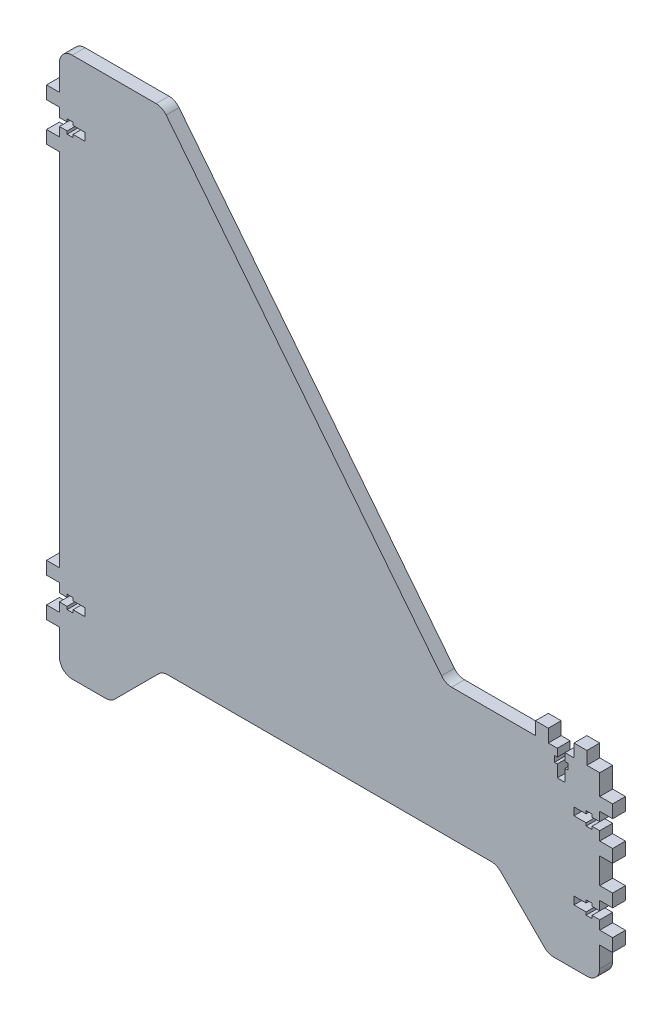
SolidWorks part; units mm, degrees
ref_plane "Plan de face" through (0, 0, 0) normal (0, 0, 1) x (1, 0, 0)
ref_plane "Plan de dessus" through (0, 0, 0) normal (0, 1, 0) x (1, 0, 0)
ref_plane "Plan de droite" through (0, 0, 0) normal (1, 0, 0) x (0, 0, -1)
sketch "Esquisse1" plane through (0, 0, 0) normal (0, 0, 1) x (1, 0, 0)
  line L0 (0, 0) -> (20, 0)
  line L1 (20, 0) -> (20, 71) construction
  line L2 (20, 71) -> (-40, 71) construction
  line L4 (-190, 210) -> (-190, 0) construction
  line L5 (-190, 0) -> (0, 0) construction
  line L6 (-190, 105) -> (56.9095, 105) construction
  line L7 (-190, 210) -> (-150, 210)
  line L8 (-150, 210) -> (-40, 71)
  line L9 (-190, 0) -> (-170, 0)
  line L10 (-170, 0) -> (-150, 20)
  line L11 (-150, 20) -> (-20, 20)
  line L12 (-20, 20) -> (0, 0)
  line L13 (-40, 71) -> (-5, 71)
  line L14 (15, 71) -> (20, 71)
  line L15 (20, 71) -> (20, 63)
  line L16 (20, 43) -> (20, 33)
  line L17 (20, 13) -> (20, 0)
  line L18 (-190, 0) -> (-190, 15)
  line L19 (-190, 35) -> (-190, 175)
  line L20 (-190, 195) -> (-190, 210)
  point P22 (0, 0)
  line B0 (17, 20.4) -> (14.7, 20.4)
  line B1 (14.7, 24.5) -> (10, 24.5)
  line B2 (10, 21.5) -> (14.7, 21.5)
  line B3 (14.7, 20.4) -> (14.7, 21.5)
  line B4 (20, 23) -> (8.7792, 23) construction
  line B5 (20, 21.5) -> (20, 18)
  line B6 (25, 18) -> (25, 13)
  line B7 (25, 13) -> (20, 13)
  line B8 (25, 18) -> (20, 18)
  line B9 (20, 24.5) -> (20, 28)
  line B10 (20, 28) -> (25, 28)
  line B11 (25, 28) -> (25, 33)
  line B12 (25, 33) -> (20, 33)
  line B13 (20, 21.5) -> (20, 24.5) construction
  line B14 (20, 24.5) -> (17, 24.5)
  line B15 (14.7, 24.5) -> (14.7, 25.6)
  line B16 (17, 25.6) -> (17, 24.5)
  line B17 (10, 24.5) -> (10, 21.5)
  line B18 (17, 21.5) -> (17, 20.4)
  line B19 (14.7, 25.6) -> (17, 25.6)
  line B20 (17, 21.5) -> (20, 21.5)
  line B21 (10, 23) -> (20, 23) construction
  line B22 (17, 50.4) -> (14.7, 50.4)
  line B23 (14.7, 54.5) -> (10, 54.5)
  line B24 (10, 51.5) -> (14.7, 51.5)
  line B25 (14.7, 50.4) -> (14.7, 51.5)
  line B26 (20, 53) -> (8.7792, 53) construction
  line B27 (20, 51.5) -> (20, 48)
  line B28 (25, 48) -> (25, 43)
  line B29 (25, 43) -> (20, 43)
  line B30 (25, 48) -> (20, 48)
  line B31 (20, 54.5) -> (20, 58)
  line B32 (20, 58) -> (25, 58)
  line B33 (25, 58) -> (25, 63)
  line B34 (25, 63) -> (20, 63)
  line B35 (20, 51.5) -> (20, 54.5) construction
  line B36 (20, 54.5) -> (17, 54.5)
  line B37 (14.7, 54.5) -> (14.7, 55.6)
  line B38 (17, 55.6) -> (17, 54.5)
  line B39 (10, 54.5) -> (10, 51.5)
  line B40 (17, 51.5) -> (17, 50.4)
  line B41 (14.7, 55.6) -> (17, 55.6)
  line B42 (17, 51.5) -> (20, 51.5)
  line B43 (10, 53) -> (20, 53) construction
  line B44 (-187, 187.6) -> (-184.7, 187.6)
  line B45 (-184.7, 183.5) -> (-180, 183.5)
  line B46 (-180, 186.5) -> (-184.7, 186.5)
  line B47 (-184.7, 187.6) -> (-184.7, 186.5)
  line B48 (-190, 185) -> (-178.7792, 185) construction
  line B49 (-190, 186.5) -> (-190, 190)
  line B50 (-195, 190) -> (-195, 195)
  line B51 (-195, 195) -> (-190, 195)
  line B52 (-195, 190) -> (-190, 190)
  line B53 (-190, 183.5) -> (-190, 180)
  line B54 (-190, 180) -> (-195, 180)
  line B55 (-195, 180) -> (-195, 175)
  line B56 (-195, 175) -> (-190, 175)
  line B57 (-190, 186.5) -> (-190, 183.5) construction
  line B58 (-190, 183.5) -> (-187, 183.5)
  line B59 (-184.7, 183.5) -> (-184.7, 182.4)
  line B60 (-187, 182.4) -> (-187, 183.5)
  line B61 (-180, 183.5) -> (-180, 186.5)
  line B62 (-187, 186.5) -> (-187, 187.6)
  line B63 (-184.7, 182.4) -> (-187, 182.4)
  line B64 (-187, 186.5) -> (-190, 186.5)
  line B65 (-180, 185) -> (-190, 185) construction
  line B66 (-187, 22.4) -> (-184.7, 22.4)
  line B67 (-184.7, 26.5) -> (-180, 26.5)
  line B68 (-180, 23.5) -> (-184.7, 23.5)
  line B69 (-184.7, 22.4) -> (-184.7, 23.5)
  line B70 (-190, 25) -> (-178.7792, 25) construction
  line B71 (-190, 23.5) -> (-190, 20)
  line B72 (-195, 20) -> (-195, 15)
  line B73 (-195, 15) -> (-190, 15)
  line B74 (-195, 20) -> (-190, 20)
  line B75 (-190, 26.5) -> (-190, 30)
  line B76 (-190, 30) -> (-195, 30)
  line B77 (-195, 30) -> (-195, 35)
  line B78 (-195, 35) -> (-190, 35)
  line B79 (-190, 23.5) -> (-190, 26.5) construction
  line B80 (-190, 26.5) -> (-187, 26.5)
  line B81 (-184.7, 26.5) -> (-184.7, 27.6)
  line B82 (-187, 27.6) -> (-187, 26.5)
  line B83 (-180, 26.5) -> (-180, 23.5)
  line B84 (-187, 23.5) -> (-187, 22.4)
  line B85 (-184.7, 27.6) -> (-187, 27.6)
  line B86 (-187, 23.5) -> (-190, 23.5)
  line B87 (-180, 25) -> (-190, 25) construction
  line B88 (7.6, 68) -> (7.6, 65.7)
  line B89 (3.5, 65.7) -> (3.5, 61)
  line B90 (6.5, 61) -> (6.5, 65.7)
  line B91 (7.6, 65.7) -> (6.5, 65.7)
  line B92 (5, 71) -> (5, 59.7792) construction
  line B93 (6.5, 71) -> (10, 71)
  line B94 (10, 76) -> (15, 76)
  line B95 (15, 76) -> (15, 71)
  line B96 (10, 76) -> (10, 71)
  line B97 (3.5, 71) -> (0, 71)
  line B98 (0, 71) -> (0, 76)
  line B99 (0, 76) -> (-5, 76)
  line B100 (-5, 76) -> (-5, 71)
  line B101 (6.5, 71) -> (3.5, 71) construction
  line B102 (3.5, 71) -> (3.5, 68)
  line B103 (3.5, 65.7) -> (2.4, 65.7)
  line B104 (2.4, 68) -> (3.5, 68)
  line B105 (3.5, 61) -> (6.5, 61)
  line B106 (6.5, 68) -> (7.6, 68)
  line B107 (2.4, 65.7) -> (2.4, 68)
  line B108 (6.5, 68) -> (6.5, 71)
  line B109 (5, 61) -> (5, 71) construction
  dimension "D1" = 190
  dimension "D2" = 20
  dimension "D3" = 210
  dimension "D4" = 34
  dimension "D5" = 30
  dimension "D6" = 71
  dimension "D7" = 18
  dimension "D8" = 15
  dimension "D9" = 60
  dimension "D10" = 20
  dimension "D11" = 20
  dimension "D12" = 20
  dimension "D13" = 20
  dimension "D14" = 40
  dimension "D15" = 160
sketch_block_instance "Insert M3 plots ep 5mm-1"
sketch_block "Insert M3 plots ep 5mm" parameters "D1"=10, "D2"=5, "D3"=5
sketch_block_instance "Decoupe Insert M3-4"
sketch_block "Decoupe Insert M3" parameters "D1"=5.2, "D2"=3, "D3"=2.3, "D4"=3, "D5"=10
sketch_block_instance "Insert M3 plots ep 5mm-3"
sketch_block_instance "Insert M3 plots ep 5mm-4"
sketch_block_instance "Insert M3 plots ep 5mm-5"
sketch_block_instance "Insert M3 plots ep 5mm-6"
extrude "Boss.-Extru.1" add sketch "Esquisse1" along normal blind 5 contours B108 B106 B88 B91 B90 B105 B89 B103 B107 B104 B102 B97 B98 B99 B100 L13 L8 L7 L20 B51 B50 B52 B49 B64 B62 B44 B47 B46 B61 B45 B59 B63 B60 B58 B53 B54 B55 B56 L19 B78 B77 B76 B75 B80 B82 B85 B81 B67 B83 B68 B69
fillet "Congé1" radius 5 9 edges at (20, 0, 2.5) (0, 0, 2.5) (-20, 20, 2.5) (-150, 20, 2.5) (-170, 0, 2.5) (-190, 0, 2.5) (-190, 210, 2.5) (-150, 210, 2.5) (-40, 71, 2.5)
